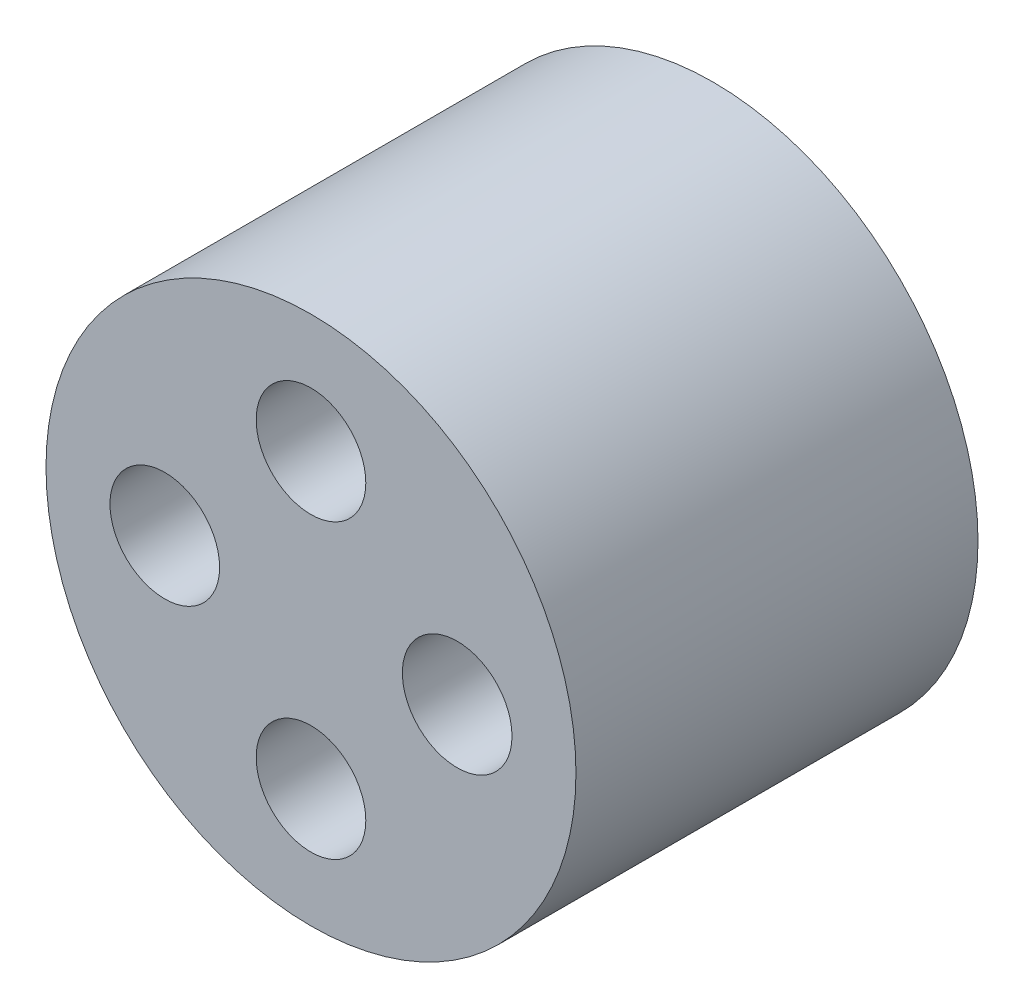
SolidWorks part; units mm, degrees
ref_plane "Ebene vorne" through (0, 0, 0) normal (0, 0, 1) x (1, 0, 0)
ref_plane "Ebene oben" through (0, 0, 0) normal (0, 1, 0) x (1, 0, 0)
ref_plane "Ebene rechts" through (0, 0, 0) normal (1, 0, 0) x (0, 0, -1)
sketch "Skizze1" plane through (0, 0, 0) normal (0, 0, 1) x (1, 0, 0)
  circle A0 centre (0, 0) radius 14.5
  circle A1 centre (0, 0) radius 8
  circle A2 centre (8, 0) radius 1.5
  circle A3 centre (0, -8) radius 1.5
  circle A4 centre (-8, 0) radius 1.5
  circle A5 centre (0, 8) radius 1.5
  point P15 (0, 0)
  dimension "D1" = 16
  dimension "D2" = 29
  dimension "D3" = 4
extrude "Aufsatz-Linear austragen1" add sketch "Skizze1" along normal blind 22 contours A0 A5 A1 A2 A3 A4 | A5 A1 A4 A3 A2
sketch "Skizze2" plane through (0, 0, 22) normal (0, 0, 1) x (1, 0, 0)
  circle A0 centre (0, 8) radius 3
  circle A1 centre (8, 0) radius 3
  circle A2 centre (0, -8) radius 3
  circle A3 centre (-8, 0) radius 3
  point P11 (0, 0)
  dimension "D1" = 4
extrude "Schnitt-Linear austragen1" cut sketch "Skizze2" against normal offset from surface (17 mm away) 5 up to face at (1.5, 8, 0)
